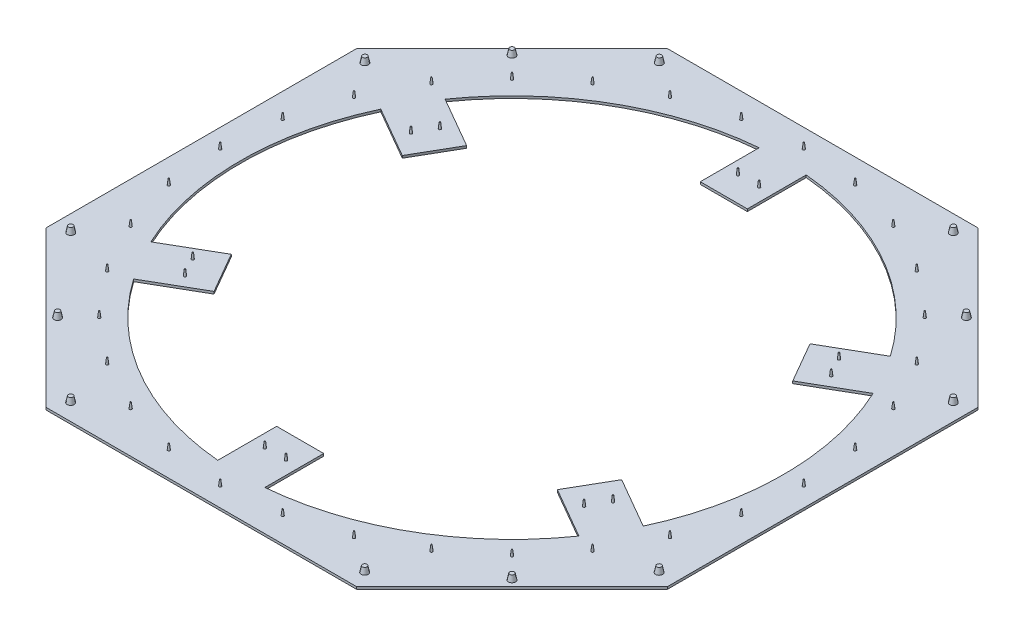
SolidWorks part; units mm, degrees
ref_plane "Front Plane" through (0, 0, 0) normal (0, 0, 1) x (1, 0, 0)
ref_plane "Top Plane" through (0, 0, 0) normal (0, 1, 0) x (1, 0, 0)
ref_plane "Right Plane" through (0, 0, 0) normal (1, 0, 0) x (0, 0, -1)
sketch "Sketch1" plane through (0, 0, 0) normal (0, 1, 0) x (1, 0, 0)
  line L7 (264, 0) -> (264, 131.98)
  line L9 (131.9796, 264) -> (0, 264)
  line L14 (131.9796, 264) -> (264, 131.98)
  line L15 (0, 264) -> (0, 0) construction
  line L16 (264, 109.3524) -> (186.6762, 186.6762) [skipped]
  line L17 (0, 0) -> (264, 0) construction
  line L18 (264, -131.9796) -> (131.98, -264)
  line L19 (-264, 0) -> (-264, -109.3524) [skipped]
  line L20 (-186.6762, 186.6762) -> (-264, 109.3524) [skipped]
  line L21 (-186.6762, -186.6762) -> (-109.3524, -264) [skipped]
  line L22 (0, -264) -> (109.3524, -264) [skipped]
  line L23 (186.6762, -186.6762) -> (264, -109.3524) [skipped]
  line L24 (264, -131.9796) -> (264, 0)
  line L25 (0, -264) -> (131.98, -264)
  line L26 (-131.9796, -264) -> (-264, -131.98)
  line L27 (-131.9796, -264) -> (0, -264)
  line L28 (-264, 0) -> (-264, -131.98)
  line L29 (-264, 131.9796) -> (-131.98, 264)
  line L30 (-264, 131.9796) -> (-264, 0)
  line L31 (0, 264) -> (-131.98, 264)
  arc A0 (264, 0) -> (0, 264) centre (0, 0) ccw construction
  point P33 (0, 0)
  dimension "D1" = 264
  dimension "D2" = 280
  dimension "D3" = 131.98
  dimension "D4" = 4
extrude "baseplate profile" add sketch "Sketch1" against normal blind 2
sketch "Sketch2" plane through (0, 0, 0) normal (0, 1, 0) x (1, 0, 0)
  line L0 (0, -248) -> (0, 248) construction
  circle A0 centre (0, 248) radius 1
  dimension "D2" = 2
  dimension "D1" = 496
extrude "M3 pins" add sketch "Sketch2" along normal blind 5 draft 7
sketch "center line" plane through (0, 0, 0) normal (0, 0, 1) x (1, 0, 0)
  line L0 (0, 0) -> (0, 200) construction
  point P3 (0, 0)
  dimension "D1" = 200
pattern_circular "CirPattern1" count 32 over 360 about axis through (0, 0, 0) along (0, 1, 0) of "M3 pins"
sketch "Sketch4" plane through (0, 0, 0) normal (0, 1, 0) x (1, 0, 0)
  line L0 (0, 0) -> (0, 201) construction
  line L1 (-9, 201) -> (9, 201) construction
  circle A0 centre (9, 201) radius 1
  circle A1 centre (-9, 201) radius 1
  point P5 (0, 201)
  dimension "D3" = 2
  dimension "D4" = 2
  dimension "D1" = 201
  dimension "D2" = 18
extrude "pillar pins" add sketch "Sketch4" along normal blind 5 draft 6
pattern_circular "CirPattern2" count 6 over 360 about axis through (0, 0, 0) along (0, 1, 0) of "pillar pins"
sketch "Sketch5" plane through (0, 0, 0) normal (0, 1, 0) x (1, 0, 0)
  line L0 (-193.0402, 193.0402) -> (193.0402, -193.0402) construction
  line L1 (-131.9796, -264) -> (131.98, -264) construction
  circle A0 centre (-193.0402, 193.0402) radius 3
  dimension "D3" = 6
  dimension "D1" = 546
  dimension "D2" = 45
extrude "M8 hole -1" add sketch "Sketch5" along normal blind 5 draft 12
pattern_circular "M8 -1 pattern" count 4 over 360 about axis through (0, 0, 0) along (0, 1, 0) of "M8 hole -1"
sketch "Sketch6" plane through (0, 0, 0) normal (0, 1, 0) x (1, 0, 0)
  line L0 (0, 0) -> (0, -324.5462) construction
  line L1 (0, 0) -> (-438.1399, 0) construction
  circle A0 centre (-125, -250) radius 3
  dimension "D1" = 6
  dimension "D2" = 125
  dimension "D3" = 250
extrude "M8 -2" add sketch "Sketch6" along normal blind 5 draft 12
pattern_circular "M8 -2 pattern" count 4 over 360 about axis through (0, 0, 0) along (0, 1, 0) of "M8 -2"
pattern_circular "M8 -3" count 2 over 36.9 about axis through (0, 0, 0) along (0, 1, 0) of "M8 -2 pattern", "M8 -2"
sketch "Sketch7" plane through (0, 0, 0) normal (0, 1, 0) x (1, 0, 0)
  line L1 (94.9211, 86.9806) -> (274.9211, 86.9806)
  line L2 (94.9211, 86.9806) -> (94.9211, -93.0194)
  line L3 (94.9211, -93.0194) -> (274.9211, -93.0194)
  line L4 (274.9211, 86.9806) -> (274.9211, -93.0194)
  dimension "D1" = 180
  dimension "D2" = 180
sketch "Sketch8" plane through (0, 0, 0) normal (0, 1, 0) x (1, 0, 0)
  line L0 (0, 0) -> (0, -180) construction
  line L1 (20, -230) -> (-20, -230)
  line L2 (20, -230) -> (20, -180)
  line L3 (20, -180) -> (-20, -180)
  line L4 (-20, -230) -> (-20, -180)
  line L5 (0, 0) -> (115.434, -199.9375)
  line L6 (0, 0) -> (-115.434, -199.9375)
  arc A0 (20, -230) -> (115.434, -199.9375) centre (0, 0) ccw
  arc A1 (-20, -230) -> (-115.434, -199.9375) centre (0, 0) cw
  point P7 (0, -180)
  dimension "D4" = 30
  dimension "D1" = 40
  dimension "D2" = 180
  dimension "D3" = 50
extrude "cut center" cut sketch "Sketch8" against normal through all contours L5 L0 L3 L2 A0 | L0 L6 A1 L4 L3
pattern_circular "CirPattern7" count 6 over 360 about axis through (0, 0, 0) along (0, 1, 0) of "cut center"
